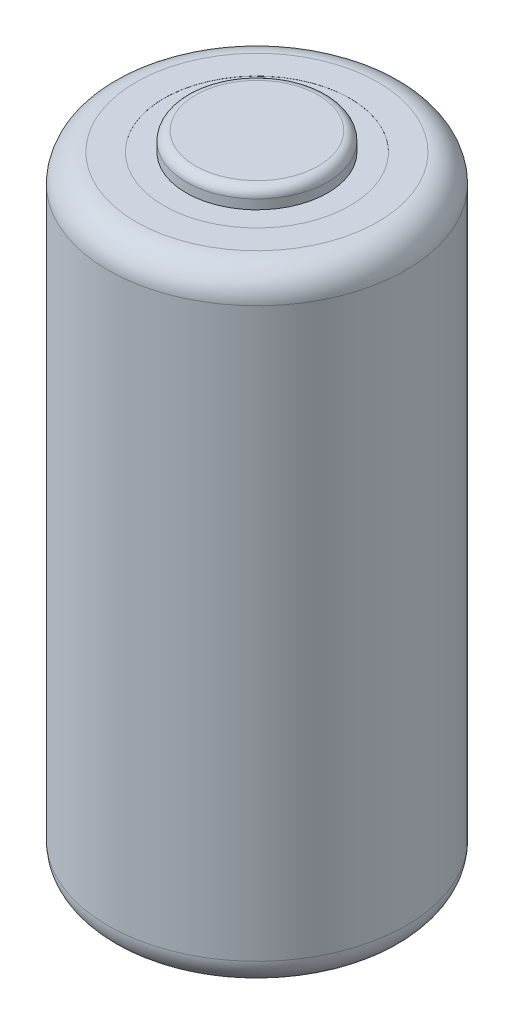
SolidWorks part; units mm, degrees
ref_plane "Ebene vorne" through (0, 0, 0) normal (0, 0, 1) x (1, 0, 0)
ref_plane "Ebene oben" through (0, 0, 0) normal (0, 1, 0) x (1, 0, 0)
ref_plane "Ebene rechts" through (0, 0, 0) normal (1, 0, 0) x (0, 0, -1)
sketch "Skizze1" plane through (0, 0, 0) normal (0, 1, 0) x (1, 0, 0)
  circle A0 centre (0, 0) radius 8
  dimension "D1" = 16
extrude "Aufsatz-Linear austragen1" add sketch "Skizze1" along normal blind 33.5
sketch "Skizze2" plane through (0, 33.5, 0) normal (0, 1, 0) x (1, 0, 0)
  circle A0 centre (0, 0) radius 3.8
extrude "Aufsatz-Linear austragen2" add sketch "Skizze2" along normal blind 1
fillet "Verrundung1" radius 1.5 2 edges at (0, 0, 8) (0, 33.5, 8)
fillet "Verrundung2" radius 0.5 1 edges at (0, 34.5, 3.8)
sketch "Skizze3" plane through (0, 33.5, 0) normal (0, 1, 0) x (1, 0, 0)
  circle A0 centre (0, 0) radius 5
  circle A1 centre (0, 0) radius 3.8
  dimension "D1" = 10
  dimension "D2" = 7.6
extrude "Schnitt-Linear austragen1" cut sketch "Skizze3" against normal blind 0.005
